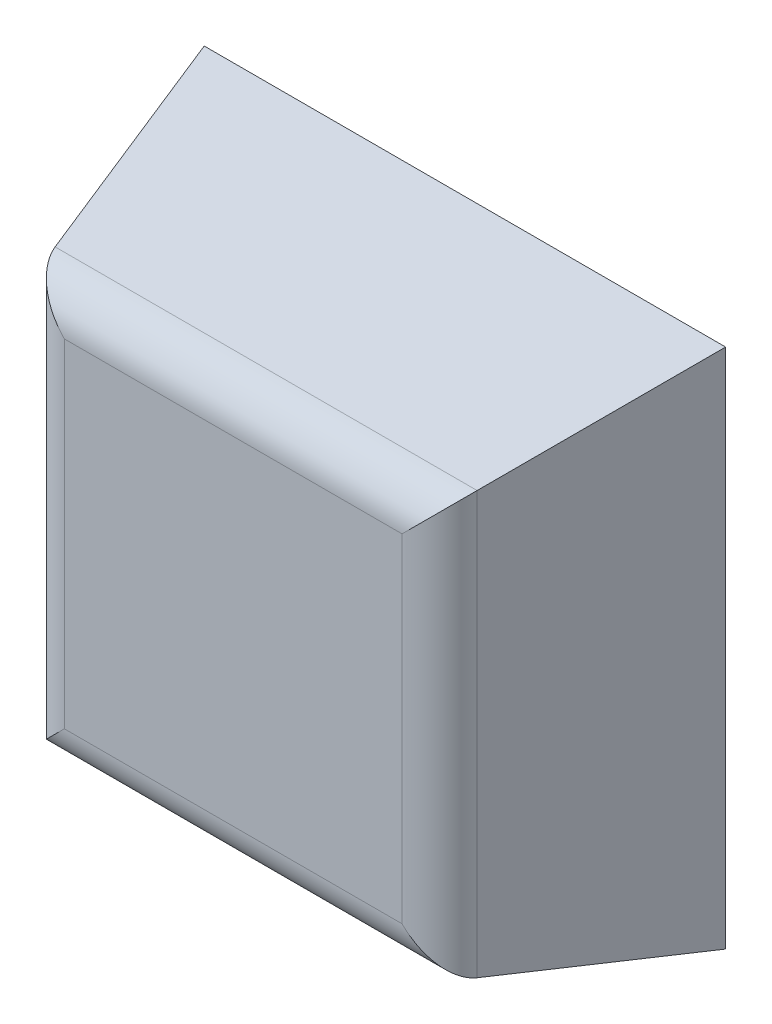
SolidWorks part; units mm, degrees
ref_plane "前视基准面" through (0, 0, 0) normal (0, 0, 1) x (1, 0, 0)
ref_plane "上视基准面" through (0, 0, 0) normal (0, 1, 0) x (1, 0, 0)
ref_plane "右视基准面" through (0, 0, 0) normal (1, 0, 0) x (0, 0, -1)
ref_plane "基准面1" through (0, 0, 8) normal (0, 0, 1) x (1, 0, 0)
sketch "草图1" plane through (0, 0, 0) normal (0, 0, 1) x (1, 0, 0)
  line L0 (-9, -9) -> (9, -9)
  line L1 (9, -9) -> (9, 9)
  line L2 (9, 9) -> (-9, 9)
  line L3 (-9, 9) -> (-9, -9)
sketch "草图2" plane through (0, 0, 8) normal (0, 0, 1) x (1, 0, 0)
  line L0 (-7, -7) -> (7, -7)
  line L1 (7, -7) -> (7, 7)
  line L2 (7, 7) -> (-7, 7)
  line L3 (-7, 7) -> (-7, -7)
loft "放样1" add profiles "草图1", "草图2"
sketch "草图3" plane through (0, 0, 0) normal (0, 0, 1) x (1, 0, 0)
  line L0 (-6, -6) -> (6, -6)
  line L1 (6, -6) -> (6, 6)
  line L2 (6, 6) -> (-6, 6)
  line L3 (-6, 6) -> (-6, -6)
extrude "切除-拉伸1" cut sketch "草图3" along normal blind 3
fillet "圆角1" radius 1.5 4 edges
